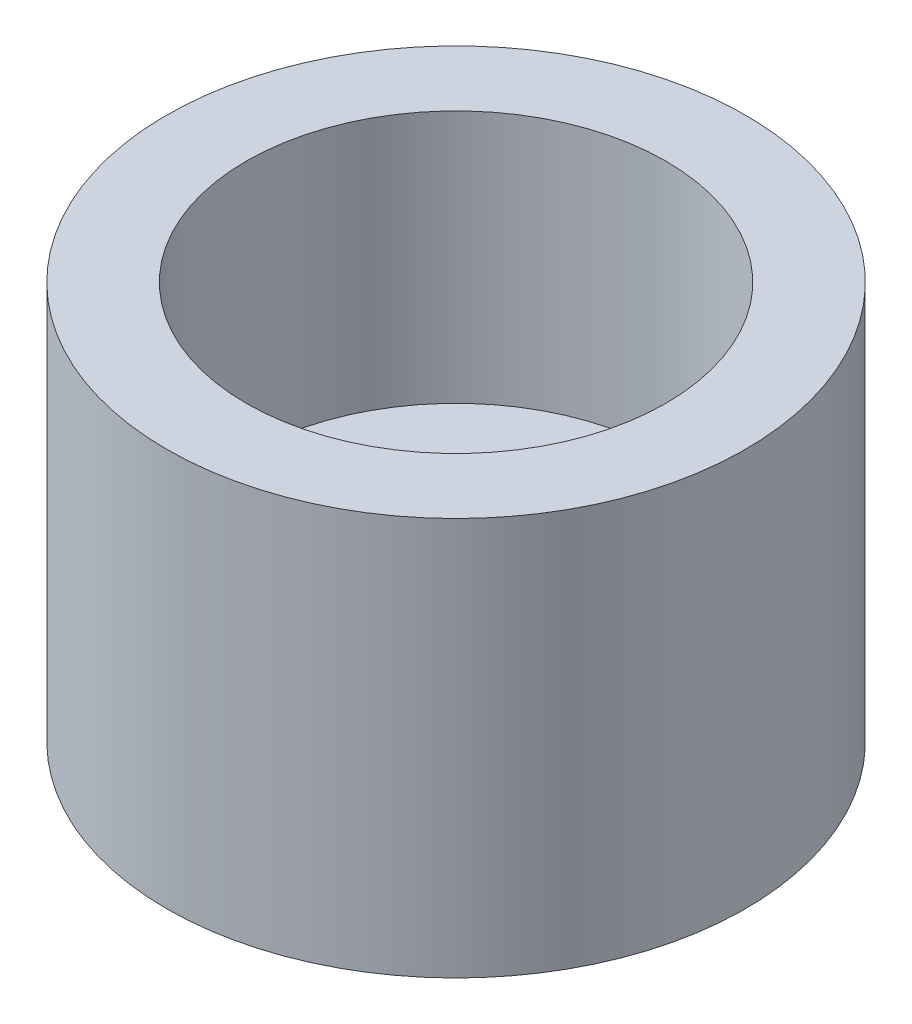
SolidWorks part; units mm, degrees
ref_plane "前视基准面" through (0, 0, 0) normal (0, 0, 1) x (1, 0, 0)
ref_plane "上视基准面" through (0, 0, 0) normal (0, 1, 0) x (1, 0, 0)
ref_plane "右视基准面" through (0, 0, 0) normal (1, 0, 0) x (0, 0, -1)
other "Configuration Table"
sketch "草图1" plane through (0, 0, 0) normal (0, 1, 0) x (1, 0, 0)
  circle A1 centre (0, 0) radius 4
  dimension "D1" = 8
extrude "凸台-拉伸1" add sketch "草图1" along normal blind 2 contours A1
sketch "草图2" plane through (0, 2, 0) normal (0, 1, 0) x (1, 0, 0)
  circle A0 centre (0, 0) radius 2.9
  circle A1 centre (0, 0) radius 4
  circle A2 centre (0, 0) radius 4 construction
  dimension "D1" = 5.8
extrude "凸台-拉伸2" add sketch "草图2" along normal blind 3.5
